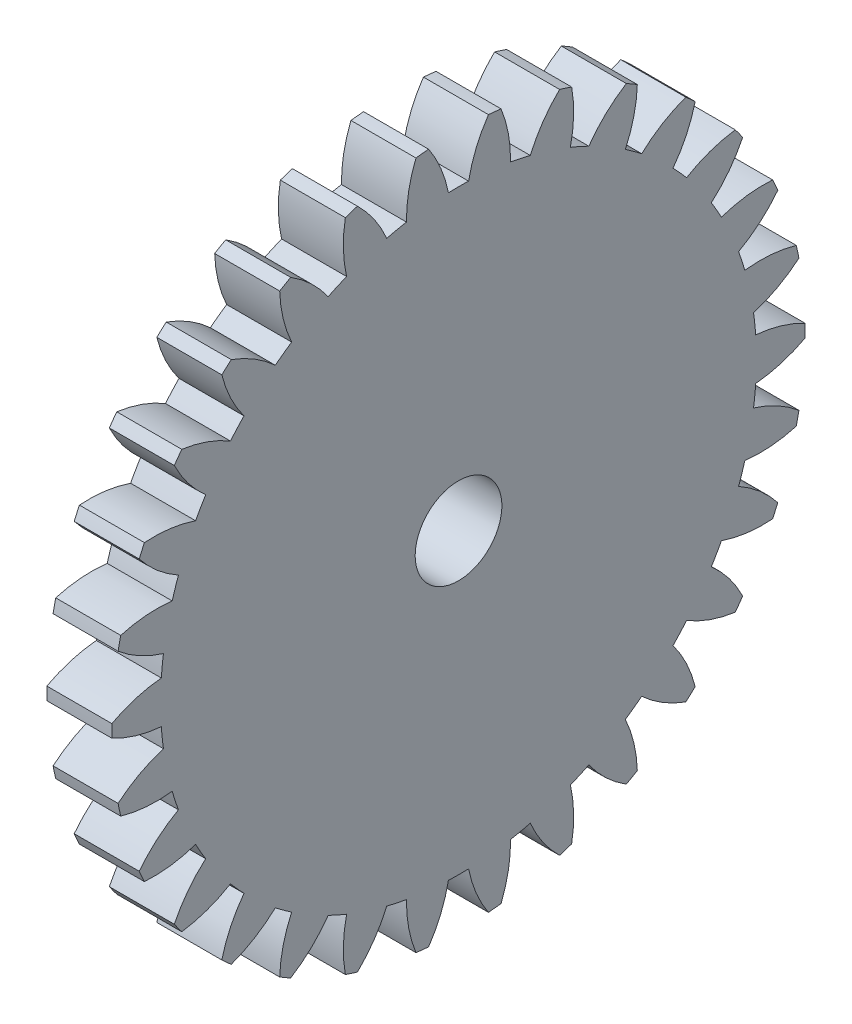
SolidWorks part; units mm, degrees
ref_plane "Plane1" through (0, 0, 0) normal (0, 0, 1) x (1, 0, 0)
ref_plane "Plane2" through (0, 0, 0) normal (0, 1, 0) x (1, 0, 0)
ref_plane "Plane3" through (0, 0, 0) normal (1, 0, 0) x (0, 0, -1)
other "Configuration Table"
sketch "HoldingSke" plane through (0, 0, 0) normal (0, 1, 0) x (1, 0, 0)
  line L0 (0, 0) -> (1.7321, -1)
  line L1 (-15, 0) -> (100, 0) construction
  line L2 (0, 0) -> (-2.1039, 2.3779)
  line L3 (0, 0) -> (-11.863, 4.5341)
  line L4 (0, 0) -> (7.479, 4.318)
  line L5 (0, 0) -> (-46.8476, -17.4728)
  line L6 (0, 0) -> (-1.2434, -0.839)
  line L7 (-2.1039, 2.3779) -> (8.6586, 51.2059)
  line L8 (-76.2, 54.61) -> (-75.9, 54.61)
  line L9 (-71.009, 38.7566) -> (-53.1078, 45.2721)
  line L10 (-76.2, 71.12) -> (104.1128, 71.12)
  line L11 (0, 0) -> (-1.5, 0)
  line L12 (-76.2, 101.6) -> (-76.181, 101.6)
  line L13 (24.9733, 27.94) -> (52.9518, 28.4284)
  line L14 (24.9733, 27.94) -> (24.9743, 27.94)
  line L15 (24.9733, 27.94) -> (100.4006, 29.5858)
  line L16 (-63.627, -0.5) -> (-12.827, -0.5)
  circle A0 centre (0, 0) radius 1
  circle A1 centre (0, 0) radius 6.874
  circle A2 centre (0, 0) radius 37.5
  circle A3 centre (0, 0) radius 1
  dimension "MHD" = 13.748
  dimension "Hub_dia" = 75
  dimension "Bore" = 2
  dimension "MBD" = 2
  dimension "Num_teeth" = 30
  dimension "Pitch" = 2
  dimension "Overall_len" = 50
  dimension "Show_teeth" = 30
  dimension "Thickness" = 1.5
  dimension "OAL" = 50.0001
  dimension "T_dim" = 0.3
  dimension "Ap" = 20
  dimension "H" = 19.05
  dimension "Pitch_radius" = 180.3128
  dimension "Width" = 1.5
  dimension "Backlash" = 0.019
  dimension "Addendum_fac" = 1
  dimension "Dedendum_fac" = 1.25
  dimension "Clearance_fac" = 0.25
  dimension "Dedendum_add" = 0.001
  dimension "Module" = 0.5
sketch "BasProSke" plane through (0, 0, 0) normal (0, 1, 0) x (1, 0, 0)
  line L0 (-10, 0) -> (60, 0) construction
  line L1 (0, 0) -> (0, 8)
  line L2 (0, 0) -> (1.5, 0)
  line L3 (1.5, 0) -> (1.5, 8)
  line L4 (1.5, 8) -> (0, 8)
  dimension "Thickness" = 1.5
  dimension "Diameter" = 16
revolve "Base-Revolve" add sketch "BasProSke" angle 360 about L0
sketch "TooCutSke" plane through (0, 0, 0) normal (1, 0, 0) x (0, 0, -1)
  line L1 (0, 0) -> (0, 107) construction
  line L2 (0, 0) -> (-0.4258, 7.4879) construction
  line L3 (0, 0) -> (-1.5661, 14.9007) construction
  line L4 (-0.4258, 7.4879) -> (-0.7831, 7.4504) construction
  arc A0 (0.2331, 6.87) -> (-0.2331, 6.87) centre (0, 0) ccw
  arc A1 (0.707, 7.9942) -> (-0.707, 7.9942) centre (0, 0) ccw
  circle A2 centre (0, 0) radius 7.5 construction
  circle A3 centre (0, 0) radius 7.0477 construction
  arc A4 (-0.2331, 6.87) -> (-0.707, 7.9942) centre (-3.1767, 6.2911) ccw
  arc A5 (0.707, 7.9942) -> (0.2331, 6.87) centre (3.1767, 6.2911) ccw
  dimension "Root_dia" = 13.748
  dimension "Overcut_dia" = 16.0508
  dimension "Pitch_dia" = 15
  dimension "Base_dia" = 14.0954
  dimension "Flank_rad" = 3
  dimension "Half_ang" = 6
  dimension "Half_CT" = 0.3593
extrude "ToothCut" cut sketch "TooCutSke" along normal through all
fillet "Breaks" [suppressed] radius 0.01
fillet "RootFillets" [suppressed] radius 0.126
pattern_circular "TeethCuts" count 30 every 12 about axis through (-10, 0, 0) along (1, 0, 0) of "ToothCut", "RootFillets", "Breaks"
sketch "HubNeaOneSke" plane through (0, 0, 0) normal (-1, 0, 0) x (0, 0, 1)
  circle A0 centre (0, 0) radius 6.874
  dimension "Diameter" = 13.748
extrude "HubNearOne" [suppressed] add sketch "HubNeaOneSke" along normal blind 48.5001
sketch "HubNeaBotSke" plane through (0, 0, 0) normal (-1, 0, 0) x (0, 0, 1)
  circle A0 centre (0, 0) radius 6.874
  dimension "Diameter" = 13.748
extrude "HubNearBoth" [suppressed] add sketch "HubNeaBotSke" along normal blind 24.25
ref_plane "FarPln" through (1.5, 0, 0) normal (1, 0, 0) x (0, 0, -1)
sketch "HubFarSke" plane through (1.5, 0, 0) normal (1, 0, 0) x (0, 0, -1)
  circle A0 centre (0, 0) radius 6.874
  dimension "Diameter" = 13.748
extrude "HubFar" [suppressed] add sketch "HubFarSke" along normal blind 24.25
sketch "BorSke" plane through (0, 0, 0) normal (1, 0, 0) x (0, 0, -1)
  circle A0 centre (0, 0) radius 1
  dimension "Diameter" = 2
extrude "Bore" cut sketch "BorSke" along normal mid plane 100.0001
sketch "KeySke" plane through (0, 0, 0) normal (1, 0, 0) x (0, 0, -1)
  line L0 (-0.4, 0) -> (-0.4, 1.3)
  line L1 (-0.4, 1.3) -> (0.4, 1.3)
  line L2 (0.4, 1.3) -> (0.4, 0)
  line L3 (0, 0) -> (0, 34) construction
  line L4 (-0.4, 0) -> (0.4, 0)
  dimension "Offset" = 1.3
  dimension "Width" = 0.8
extrude "Keyway" [suppressed] cut sketch "KeySke" along normal mid plane 100.0001
pattern_circular "Keyway2" [suppressed] count 2 every 90 about axis through (-10, 0, 0) along (1, 0, 0)
equation "' \"Module@HoldingSke\" = 6.35"
equation "' \"Num_teeth@HoldingSke\" = 12"
equation "' \"Ap@HoldingSke\" =  20"
equation "' \"Ap@HoldingSke\" = 20"
equation "' \"Width@HoldingSke\" = 0.5 * 25.4"
equation "' \"Hub_dia@HoldingSke\"= 1 * 25.4"
equation "' \"Hub_dia@HoldingSke\" = 1 * 25.4"
equation "' \"Overall_len@HoldingSke\" = 1.0 * 25.4"
equation "' \"Bore@HoldingSke\" = 0.75 * 25.4"
equation "' \"T_dim@HoldingSke\" = 0.1 * 25.4"
equation "' \"Width@KeySke\" = 0.25 * 25.4"
equation "' \"Show_teeth@HoldingSke\" = 13"
equation "' \"Backlash@HoldingSke\" = 0.009 * 25.4"
equation "' \"Addendum_fac@HoldingSke\" = 1.0"
equation "' \"Dedendum_fac@HoldingSke\" = 1.25"
equation "' \"Dedendum_add@HoldingSke\" = 0.00005 * 25.4"
equation "' \"Clearance_fac@HoldingSke\" = 0.25"
equation "\"Pitch@HoldingSke\" = 1 / \"Module@HoldingSke\""
equation "\"Overcut_dia@TooCutSke\" = (\"Num_teeth@HoldingSke\" + 2 * \"Addendum_fac@HoldingSke\") / \"Pitch@HoldingSke\" + 0.002 * 25.4"
equation "\"Pitch_dia@TooCutSke\" = \"Num_teeth@HoldingSke\" / \"Pitch@HoldingSke\""
equation "\"Base_dia@TooCutSke\" = \"Num_teeth@HoldingSke\" / \"Pitch@HoldingSke\" * cos((\"Ap@HoldingSke\"  * 3.14159265 / 180))"
equation "\"Root_dia@TooCutSke\" = (\"Num_teeth@HoldingSke\" + 2) / \"Pitch@HoldingSke\" - 2 * (\"Addendum_fac@HoldingSke\" + \"Dedendum_fac@HoldingSke\") / \"Pitch@HoldingSke\" - \"Dedendum_add@HoldingSke\" * 2"
equation "\"Half_ang@TooCutSke\" = 180 / \"Num_teeth@HoldingSke\""
equation "\"Half_CT@TooCutSke\" = \"Num_teeth@HoldingSke\" / \"Pitch@HoldingSke\" * sin((3.14159265 / 2 / \"Num_teeth@HoldingSke\")) / 2 - 7 * \"Backlash@HoldingSke\" / 4"
equation "\"Flank_rad@TooCutSke\" = \"Num_teeth@HoldingSke\" / \"Pitch@HoldingSke\" / 5"
equation "\"Radius@RootFillets\" = \"Clearance_fac@HoldingSke\" / \"Pitch@HoldingSke\" + \"Dedendum_add@HoldingSke\""
equation "\"Break_rad@Breaks\" = 0.02 / \"Pitch@HoldingSke\""
equation "\"Thickness@HoldingSke\" = \"Width@HoldingSke\""
equation "\"OAL@HoldingSke\" = \"Thickness@HoldingSke\""
equation "\"MHD@HoldingSke\" = (\"Num_teeth@HoldingSke\" + 2) / \"Pitch@HoldingSke\" - 2 * (\"Addendum_fac@HoldingSke\" + \"Dedendum_fac@HoldingSke\")  / \"Pitch@HoldingSke\" - \"Dedendum_add@HoldingSke\" * 2"
equation "\"MBD@HoldingSke\" = (\"Num_teeth@HoldingSke\" + 2) / \"Pitch@HoldingSke\" - 2 * (\"Addendum_fac@HoldingSke\" + \"Dedendum_fac@HoldingSke\")  / \"Pitch@HoldingSke\" - \"Dedendum_add@HoldingSke\" * 2 - 0.002 * 25.4"
equation "\"MHD@HoldingSke\" = ((sgn( \"MHD@HoldingSke\" - \"Hub_dia@HoldingSke\" )-1)*( \"MHD@HoldingSke\" - \"Hub_dia@HoldingSke\" ))/-2+ \"Hub_dia@HoldingSke\""
equation "\"MBD@HoldingSke\" = ((sgn( \"MBD@HoldingSke\" - \"Bore@HoldingSke\" )-1)*( \"MBD@HoldingSke\" - \"Bore@HoldingSke\" ))/-2+ \"Bore@HoldingSke\""
equation "\"OAL@HoldingSke\" = ((sgn( \"OAL@HoldingSke\" - \"Overall_len@HoldingSke\" )+1)*( \"OAL@HoldingSke\" - \"Overall_len@HoldingSke\" ))/2 + \"Overall_len@HoldingSke\" + 0.000002 * 25.4"
equation "\"Num_teeth@TeethCuts\" = int( \"Show_teeth@HoldingSke\" ) + 1"
equation "\"Num_teeth@TeethCuts\" = ((sgn( \"Num_teeth@TeethCuts\" - \"Num_teeth@HoldingSke\" )-1)*( \"Num_teeth@TeethCuts\" - \"Num_teeth@HoldingSke\" ))/-2+ \"Num_teeth@HoldingSke\""
equation "\"Num_teeth@TeethCuts\" = ((sgn( \"Num_teeth@TeethCuts\" - 2.0)+1)*( \"Num_teeth@TeethCuts\" - 2.0))/2 +2.0"
equation "\"Angle@TeethCuts\" = 360.0 / \"Num_teeth@HoldingSke\""
equation "\"Diameter@BasProSke\" = (\"Num_teeth@HoldingSke\" + 2 * \"Addendum_fac@HoldingSke\") / \"Pitch@HoldingSke\""
equation "\"Thickness@BasProSke\"  = \"Thickness@HoldingSke\""
equation "' \"Fillet_rad@BasProSke\" =  \"Thickness@HoldingSke\" * 0.05"
equation "' \"Fillet_rad@BasProSke\" = \"Thickness@HoldingSke\" * 0.05"
equation "\"MHD@HoldingSke\" = ((sgn( \"MHD@HoldingSke\" - \"Root_dia@TooCutSke\" )-1)*( \"MHD@HoldingSke\" - \"Root_dia@TooCutSke\" ))/-2+ \"Root_dia@TooCutSke\""
equation "\"Diameter@HubNeaOneSke\" = \"MHD@HoldingSke\""
equation "\"Length@HubNearOne\" = \"OAL@HoldingSke\" - \"Thickness@BasProSke\""
equation "\"Diameter@HubNeaBotSke\" = \"MHD@HoldingSke\""
equation "\"Length@HubNearBoth\" = ( \"OAL@HoldingSke\" - \"Thickness@BasProSke\" ) / 2.0"
equation "\"Thickness@FarPln\" = \"Thickness@BasProSke\""
equation "\"Diameter@HubFarSke\" = \"MHD@HoldingSke\""
equation "\"Length@HubFar\" = ( \"OAL@HoldingSke\" - \"Thickness@BasProSke\" ) / 2.0"
equation "\"Diameter@BorSke\" = \"MBD@HoldingSke\""
equation "\"D1@Bore\" = \"OAL@HoldingSke\" * 2.0"
equation "\"D1@Keyway\" = \"OAL@HoldingSke\" * 2.0"
equation "\"Offset@KeySke\" = \"T_dim@HoldingSke\" + \"MBD@HoldingSke\" / 2.0"
